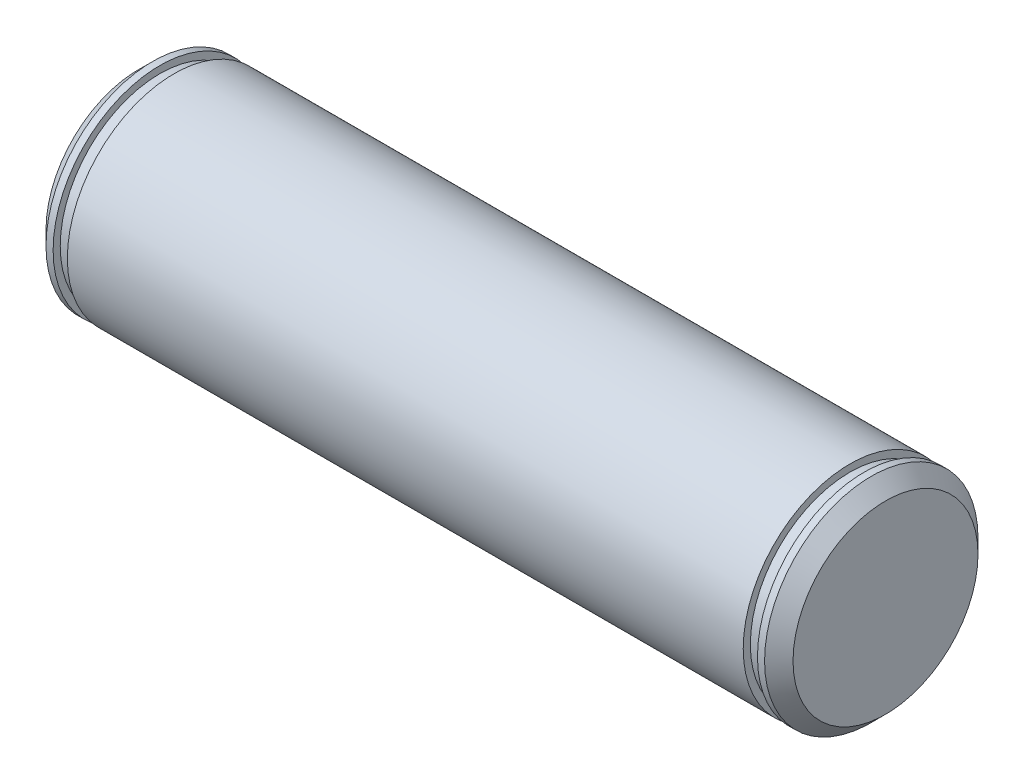
SolidWorks part; units mm, degrees
ref_plane "Front Plane" through (0, 0, 0) normal (0, 0, 1) x (1, 0, 0)
ref_plane "Top Plane" through (0, 0, 0) normal (0, 1, 0) x (1, 0, 0)
ref_plane "Right Plane" through (0, 0, 0) normal (1, 0, 0) x (0, 0, -1)
sketch "Sketch1" plane through (0, 0, 0) normal (0, 0, 1) x (1, 0, 0)
  line L0 (0, 0) -> (21326.4382, 0) construction
  line L1 (0, 0) -> (0, -21326.4382) construction
  line L2 (-52.5, 0) -> (-52.5, 13)
  line L3 (-50.5, 15) -> (-49.5, 15)
  line L4 (-49.5, 15) -> (-49.5, 14)
  line L5 (-49.5, 14) -> (-47.5, 14)
  line L6 (-47.5, 14) -> (-47.5, 15)
  line L7 (-47.5, 15) -> (47.5, 15)
  line L8 (-52.5, 13) -> (-50.5, 15)
  line L9 (47.5, 14) -> (47.5, 15)
  line L10 (49.5, 14) -> (47.5, 14)
  line L11 (49.5, 15) -> (49.5, 14)
  line L12 (50.5, 15) -> (49.5, 15)
  line L13 (52.5, 13) -> (50.5, 15)
  line L14 (52.5, 0) -> (52.5, 13)
  line L15 (-52.5, 0) -> (52.5, 0)
  point P6 (-52.5, 15)
  point P16 (0, 15)
  dimension "D1" = 2
  dimension "D2" = 105
  dimension "D3" = 3
  dimension "D4" = 28
  dimension "D5" = 30
  dimension "D6" = 2
  dimension "D7" = 45
revolve "Revolve1" add sketch "Sketch1" angle 360 about L15
